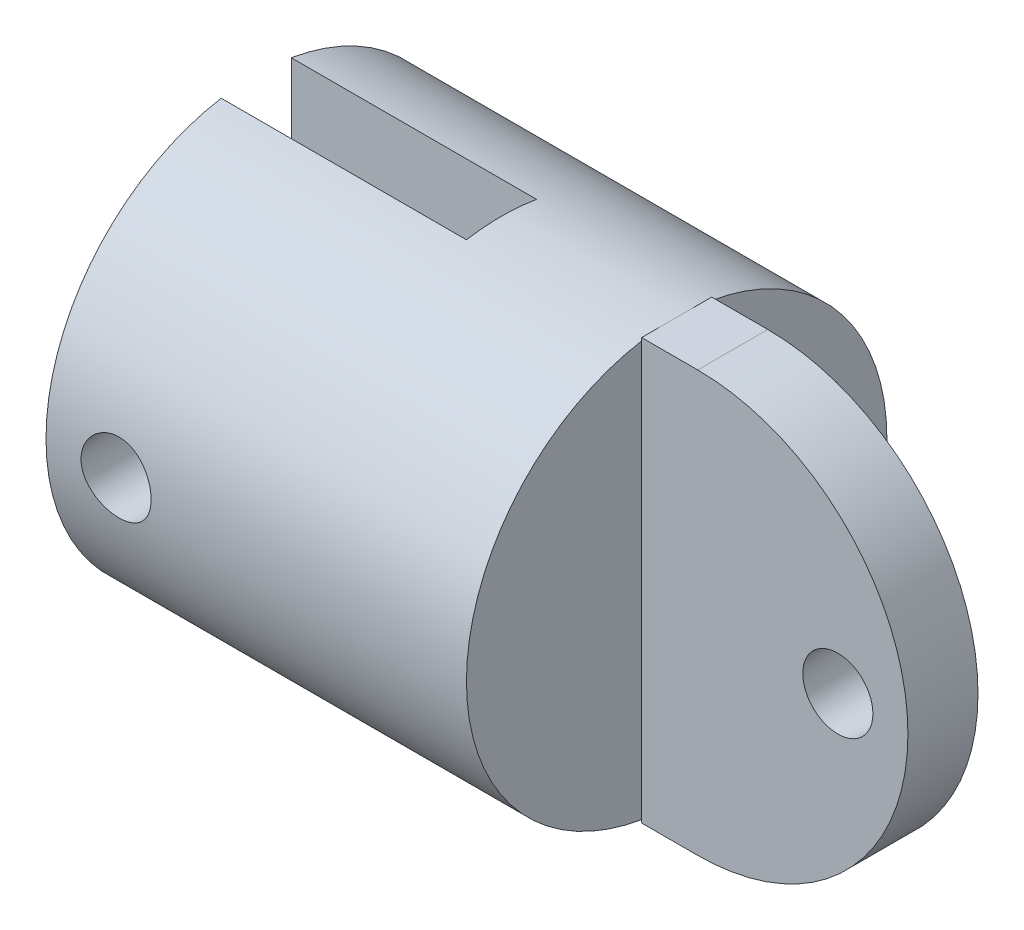
SolidWorks part; units mm, degrees
ref_plane "Front Plane" through (0, 0, 0) normal (0, 0, 1) x (1, 0, 0)
ref_plane "Top Plane" through (0, 0, 0) normal (0, 1, 0) x (1, 0, 0)
ref_plane "Right Plane" through (0, 0, 0) normal (1, 0, 0) x (0, 0, -1)
sketch "Sketch2" plane through (0, 0, 0) normal (1, 0, 0) x (0, 0, -1)
  circle A0 centre (0, 0) radius 15
  dimension "D1" = 30
extrude "Boss-Extrude1" add sketch "Sketch2" against normal blind 30
sketch "Sketch3" plane through (0, 0, 0) normal (0, 1, 0) x (1, 0, 0)
  line L0 (-30, 15) -> (-30, -15) construction
  line L1 (-30, 2.5) -> (-12.5, 2.5)
  line L2 (-30, 2.5) -> (-30, -2.5)
  line L3 (-30, -2.5) -> (-12.5, -2.5)
  line L4 (-12.5, 2.5) -> (-12.5, -2.5)
  line L5 (0, 15) -> (-30, 15) construction
  dimension "D1" = 5
  dimension "D2" = 17.5
  dimension "D3" = 0
  dimension "D4" = 12.5
extrude "Cut-Extrude1" cut sketch "Sketch3" against normal through all and the other way through all
sketch "Sketch6" plane through (0, 0, 0) normal (0, 0, 1) x (1, 0, 0)
  line L0 (-30, 14.7902) -> (-30, -14.7902) construction
  circle A0 centre (-25, 0) radius 2.5
  dimension "D2" = 5
  dimension "D1" = 5
  dimension "D3" = 0
extrude "Cut-Extrude2" cut sketch "Sketch6" against normal through all and the other way through all
sketch "Sketch7" plane through (0, 0, 0) normal (1, 0, 0) x (0, 0, -1)
  line L0 (-2.5, 15) -> (-2.5, -15)
  line L1 (-2.5, 15) -> (2.5, 15)
  line L2 (-2.5, -15) -> (2.5, -15)
  line L3 (2.5, 15) -> (2.5, -15)
  line L4 (-2.5, 15) -> (2.5, -15) construction
  line L5 (-2.5, -15) -> (2.5, 15) construction
  point P1 (0, 0)
  dimension "D1" = 5
  dimension "D2" = 30
extrude "Boss-Extrude2" add sketch "Sketch7" along normal blind 4
sketch "Sketch8" plane through (0, 0, 2.5) normal (0, 0, 1) x (1, 0, 0)
  line L0 (4, 15) -> (4, -15) construction
  line L1 (4, 15) -> (4, -15)
  arc A0 (4, -15) -> (4, 15) centre (4, 0) ccw
extrude "Boss-Extrude3" add sketch "Sketch8" against normal blind 5 contours A0 L1
sketch "Sketch9" plane through (0, 0, 2.5) normal (0, 0, 1) x (1, 0, 0)
  circle A0 centre (14, 0) radius 2.5
  arc A1 (4, -15) -> (4, 15) centre (4, 0) ccw construction
  point P5 (19, 0)
  dimension "D1" = 5
  dimension "D2" = 5
extrude "Cut-Extrude3" cut sketch "Sketch9" against normal through all and the other way through all
